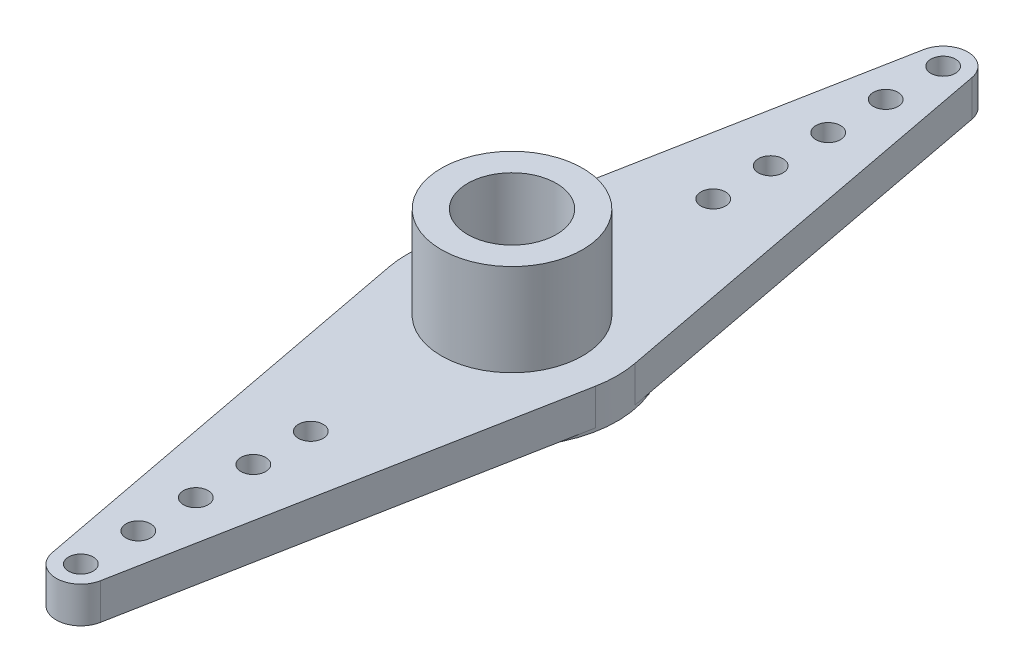
SolidWorks part; units mm, degrees
ref_plane "Front Plane" through (0, 0, 0) normal (0, 0, 1) x (1, 0, 0)
ref_plane "Top Plane" through (0, 0, 0) normal (0, 1, 0) x (1, 0, 0)
ref_plane "Right Plane" through (0, 0, 0) normal (1, 0, 0) x (0, 0, -1)
sketch "Sketch1" plane through (0, 0, 0) normal (0, 1, 0) x (1, 0, 0)
  line L0 (0, 0) -> (1.5, 0) construction
  line L1 (-1.4736, 26.53) -> (-6.2875, 1.1947)
  line L2 (1.4736, 26.53) -> (6.2875, 1.1947)
  line L3 (1.4736, -26.53) -> (6.2875, -1.1947)
  line L4 (-1.4736, -26.53) -> (-6.2875, -1.1947)
  circle A0 centre (0, 0) radius 1.5
  arc A1 (-6.2875, 1.1947) -> (-6.2875, -1.1947) centre (0, 0) ccw
  arc A2 (1.4736, 26.53) -> (-1.4736, 26.53) centre (0, 26.25) ccw
  arc A3 (-1.4736, -26.53) -> (1.4736, -26.53) centre (0, -26.25) ccw
  arc A4 (6.2875, -1.1947) -> (6.2875, 1.1947) centre (0, 0) ccw
  dimension "D1" = 3
  dimension "D2" = 12.8
  dimension "D3" = 26.25
extrude "Boss-Extrude1" add sketch "Sketch1" along normal blind 2.2
sketch "Sketch3" plane through (0, 2.2, 0) normal (0, 1, 0) x (1, 0, 0)
  circle A0 centre (0, 0) radius 2.7
  circle A1 centre (0, 0) radius 4.3
  dimension "D1" = 5.4
  dimension "D2" = 8.6
extrude "Boss-Extrude2" add sketch "Sketch3" along normal blind 5.6
sketch "Sketch4" plane through (0, 0, 0) normal (0, -1, 0) x (1, 0, 0)
  circle A0 centre (0, 0) radius 2.7
  circle A1 centre (0, 0) radius 6.4
  dimension "D1" = 5.4
  dimension "D2" = 12.8
extrude "Boss-Extrude3" add sketch "Sketch4" along normal blind 0.2
sketch "Sketch7" plane through (0, 0, 0) normal (0, -1, 0) x (1, 0, 0)
  circle A1 centre (0, 0) radius 2.7
  circle A2 centre (0, 0) radius 2.7
  dimension "D1" = 0
extrude "Cut-Extrude1" cut sketch "Sketch7" against normal blind 1.5
sketch "Sketch8" plane through (0, 0, 0) normal (0, -1, 0) x (1, 0, 0)
  circle A0 centre (0, 12.25) radius 0.75
  point P2 (0, 0)
  dimension "D1" = 12.25
  dimension "D2" = 1.5
extrude "Cut-Extrude2" cut sketch "Sketch8" against normal up to next
pattern_linear "LPattern1" count 5 spacing 3.5 along (0, 0, 1) of "Cut-Extrude2"
mirror "Mirror1" about plane through (0, 0, 0) normal (0, 0, 1) of "LPattern1", "Cut-Extrude2"
